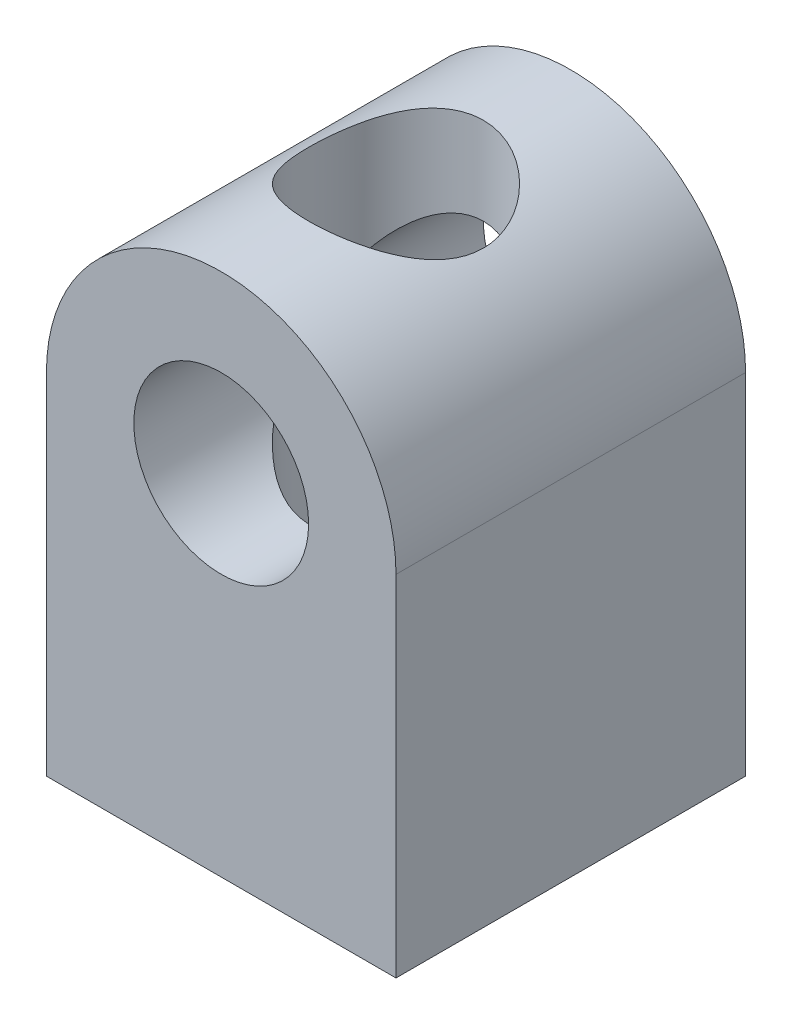
SolidWorks part; units mm, degrees
ref_plane "前视基准面" through (0, 0, 0) normal (0, 0, 1) x (1, 0, 0)
ref_plane "上视基准面" through (0, 0, 0) normal (0, 1, 0) x (1, 0, 0)
ref_plane "右视基准面" through (0, 0, 0) normal (1, 0, 0) x (0, 0, -1)
other "Configuration Table"
sketch "Sketch1" plane through (0, 0, 0) normal (0, 0, 1) x (1, 0, 0)
  line L0 (-2.5, 0) -> (-2.5, -5)
  line L1 (-2.5, -5) -> (2.5, -5)
  line L2 (2.5, -5) -> (2.5, 0)
  circle A0 centre (0, 0) radius 1.25
  circle A1 centre (0, 0) radius 2.5
  dimension "D1" = 5
  dimension "D2" = 2.5
  dimension "D3" = 5
extrude "Boss-Extrude1" add sketch "Sketch1" along normal blind 5 contours A1 L0 L1 L2 | A1 A0
sketch "Sketch2" plane through (0, -5, 0) normal (0, -1, 0) x (1, 0, 0)
  line L0 (0, 5) -> (0, 0) construction
  line L1 (-2.5, 5) -> (2.5, 5) construction
  line L2 (0, 0) -> (0, 2.5) construction
  circle A0 centre (0, 2.5) radius 1.25
  dimension "D1" = 2.5
extrude "Cut-Extrude1" cut sketch "Sketch2" against normal through all
